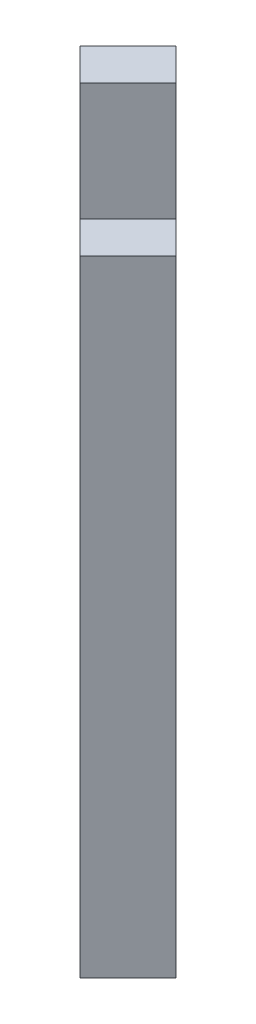
SolidWorks part; units mm, degrees
ref_plane "前视基准面" through (0, 0, 0) normal (0, 0, 1) x (1, 0, 0)
ref_plane "上视基准面" through (0, 0, 0) normal (0, 1, 0) x (1, 0, 0)
ref_plane "右视基准面" through (0, 0, 0) normal (1, 0, 0) x (0, 0, -1)
sketch "草图1" plane through (0, 0, 0) normal (0, 1, 0) x (1, 0, 0)
  line L20 (0, 0) -> (0, 106.1612) construction
  line L21 (0, 0) -> (94.5244, 0) construction
  line L22 (505, 220) -> (483.7868, 198.7868)
  line L23 (403.7868, 278.7868) -> (483.7868, 198.7868)
  line L24 (425, 300) -> (403.7868, 278.7868)
  line L25 (505, 220) -> (425, 300)
  point P3 (-505, 300)
  point P5 (505, 300)
  point P6 (505, -300)
  point P7 (-505, -300)
extrude "凸台-拉伸1" add sketch "草图1" along normal blind 275
sketch "草图4" plane through (362.5, 0, -362.5) normal (0.7071, 0, -0.7071) x (-0.7071, 0, -0.7071)
  line L0 (-181.5254, 275) -> (-108.3883, 275)
  line L1 (-201.5254, 275) -> (-88.3883, 275) construction
  line L2 (-181.5254, 275) -> (-181.5254, 150)
  line L3 (-201.5254, 137.5) -> (-88.3883, 137.5) construction
  line L4 (-108.3883, 275) -> (-108.3883, 150)
  line L5 (-108.3883, 150) -> (-181.5254, 150)
  line L6 (-201.5254, 275) -> (-201.5254, 0) construction
  line L7 (-88.3883, 275) -> (-88.3883, 0) construction
  line L8 (-181.5254, 0) -> (-181.5254, 125)
  line L9 (-108.3883, 125) -> (-181.5254, 125)
  line L10 (-108.3883, 0) -> (-108.3883, 125)
  line L11 (-181.5254, 0) -> (-108.3883, 0)
extrude "切除-拉伸3" cut sketch "草图4" against normal blind 30
sketch "草图5" plane through (0, 275, 0) normal (0, 1, 0) x (1, 0, 0)
  circle A0 centre (487.3223, 216.4645) radius 10
